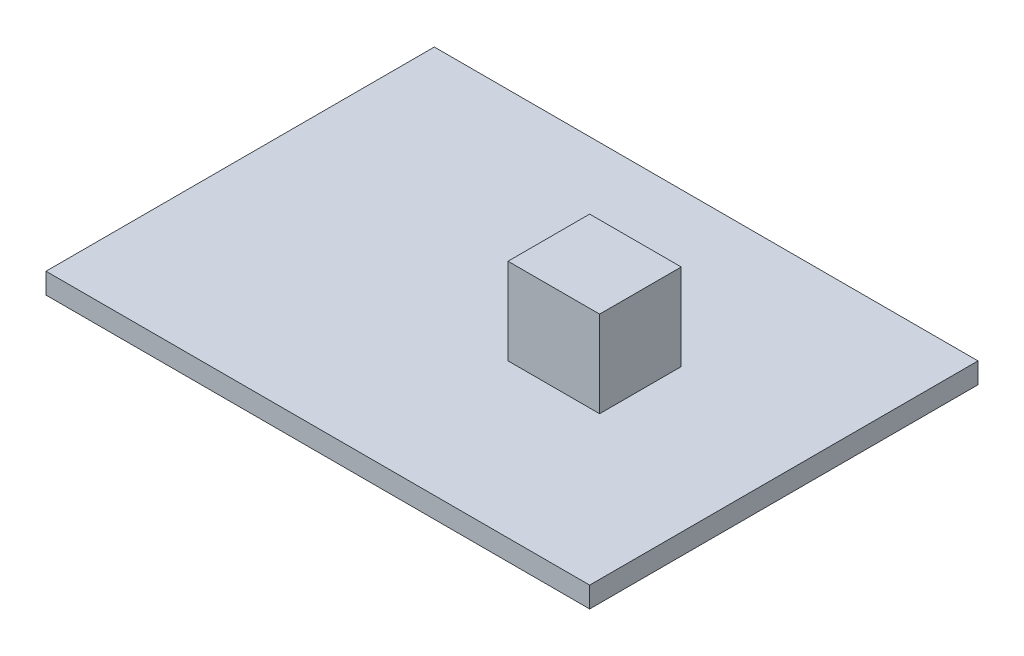
SolidWorks part; units mm, degrees
ref_plane "Front Plane" through (0, 0, 0) normal (0, 0, 1) x (1, 0, 0)
ref_plane "Top Plane" through (0, 0, 0) normal (0, 1, 0) x (1, 0, 0)
ref_plane "Right Plane" through (0, 0, 0) normal (1, 0, 0) x (0, 0, -1)
sketch "Sketch1" plane through (0, 0, 0) normal (0, 1, 0) x (1, 0, 0)
  line L1 (-35.9213, 23) -> (27.0787, 23)
  line L2 (-35.9213, 23) -> (-35.9213, -22)
  line L3 (-35.9213, -22) -> (27.0787, -22)
  line L4 (27.0787, 23) -> (27.0787, -22)
  dimension "D1" = 45
  dimension "D2" = 63
extrude "Boss-Extrude1" add sketch "Sketch1" along normal blind 2.4
sketch "Sketch3" plane through (0, 2.4, 0) normal (0, 1, 0) x (1, 0, 0)
  line L0 (-56.3565, 0.5) -> (51.0953, 0.5) construction
  line L1 (-0.154, 5.2295) -> (10.4597, 5.2295)
  line L2 (-0.154, 5.2295) -> (-0.154, -4.2295)
  line L3 (-0.154, -4.2295) -> (10.4597, -4.2295)
  line L4 (10.4597, 5.2295) -> (10.4597, -4.2295)
  line L5 (27.0787, 23) -> (-35.9213, 23) construction
  line L6 (-35.9213, -22) -> (27.0787, -22) construction
extrude "Boss-Extrude2" add sketch "Sketch3" along normal blind 10
